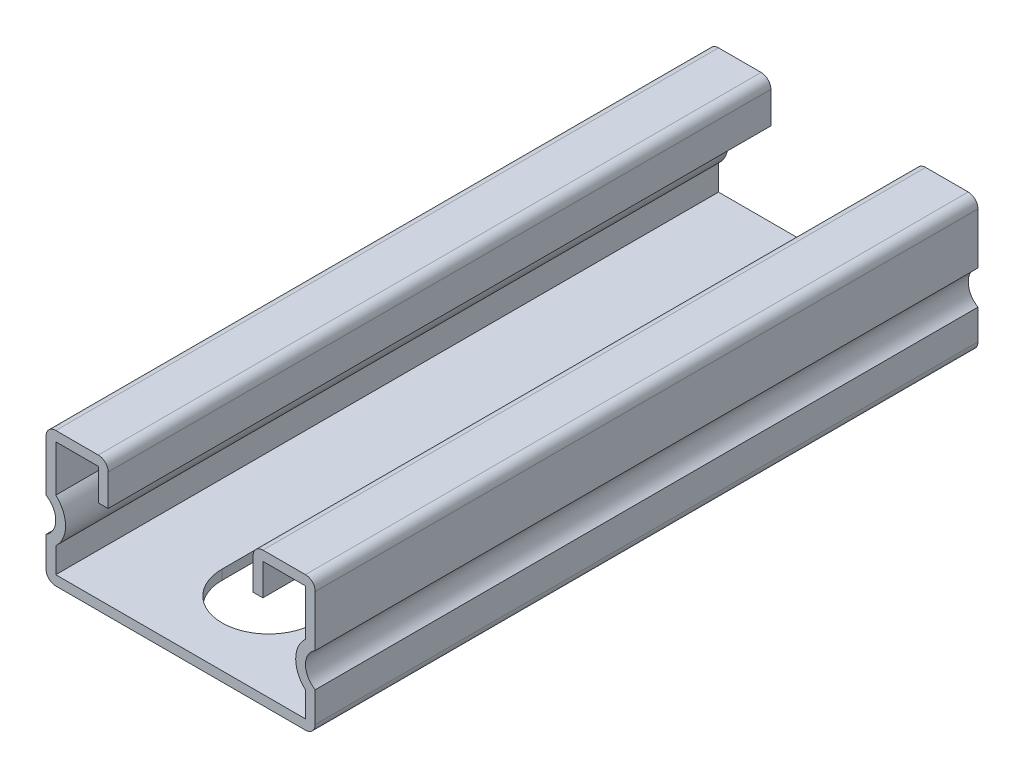
SolidWorks part; units mm, degrees
ref_plane "Plane1" through (0, 0, 0) normal (0, 0, 1) x (1, 0, 0)
ref_plane "Plane2" through (0, 0, 0) normal (0, 1, 0) x (1, 0, 0)
ref_plane "Plane3" through (0, 0, 0) normal (1, 0, 0) x (0, 0, -1)
sketch "Sketch1" plane through (0, 0, 0) normal (0, 0, 1) x (1, 0, 0)
  line L0 (-20.6375, 10.4394) -> (-20.6375, 2.5957)
  line L1 (-20.6375, -2.5957) -> (-20.6375, -7.2136)
  line L2 (-19.1389, -8.7122) -> (19.1389, -8.7122)
  line L3 (20.6375, -7.2136) -> (20.6375, -2.5957)
  line L4 (20.6375, 2.5957) -> (20.6375, 10.4394)
  line L5 (19.1389, 11.938) -> (12.6111, 11.938)
  line L6 (11.1125, 10.4394) -> (11.1125, 5.588)
  line L7 (-19.1389, 11.938) -> (-12.6111, 11.938)
  line L8 (-11.1125, 10.4394) -> (-11.1125, 5.588)
  line L9 (19.1389, -5.2823) -> (19.1389, 6.4389) construction
  line L10 (-19.1389, 6.4389) -> (-19.1389, -5.2823) construction
  line L11 (-12.6111, 10.4394) -> (-12.6111, 5.588)
  line L12 (-19.1389, 10.4394) -> (-12.6111, 10.4394)
  line L13 (-19.1389, 10.4394) -> (-19.1389, 3.351)
  line L14 (-19.1389, -3.351) -> (-19.1389, -7.2136)
  line L15 (-19.1389, -7.2136) -> (19.1389, -7.2136)
  line L16 (19.1389, -7.2136) -> (19.1389, -3.351)
  line L17 (19.1389, 3.351) -> (19.1389, 10.4394)
  line L18 (19.1389, 10.4394) -> (12.6111, 10.4394)
  line L19 (12.6111, 10.4394) -> (12.6111, 5.588)
  line L20 (-12.6111, 5.588) -> (-11.1125, 5.588)
  line L21 (11.1125, 5.588) -> (12.6111, 5.588)
  arc A0 (20.6375, 2.5957) -> (20.6375, -2.5957) centre (22.1361, 0) ccw
  arc A1 (-20.6375, -2.5957) -> (-20.6375, 2.5957) centre (-22.1361, 0) ccw
  arc A2 (-12.6111, 11.938) -> (-11.1125, 10.4394) centre (-12.6111, 10.4394) cw
  arc A3 (-20.6375, 10.4394) -> (-19.1389, 11.938) centre (-19.1389, 10.4394) cw
  arc A4 (-19.1389, -8.7122) -> (-20.6375, -7.2136) centre (-19.1389, -7.2136) cw
  arc A5 (20.6375, -7.2136) -> (19.1389, -8.7122) centre (19.1389, -7.2136) cw
  arc A6 (19.1389, 11.938) -> (20.6375, 10.4394) centre (19.1389, 10.4394) cw
  arc A7 (11.1125, 10.4394) -> (12.6111, 11.938) centre (12.6111, 10.4394) cw
  arc A8 (-19.1389, -3.351) -> (-19.1389, 3.351) centre (-22.1361, 0) ccw
  arc A9 (19.1389, 3.351) -> (19.1389, -3.351) centre (22.1361, 0) ccw
  dimension "D9" = 2.9972
  dimension "D10" = 2.9972
  dimension "D1" = 20.6375
  dimension "Width" = 41.275
  dimension "base" = 8.7122
  dimension "ToeHt" = 11.938
  dimension "D6" = 22.225
  dimension "edge" = 9.525
  dimension "Lip" = 6.35
  dimension "gauge" = 1.4986
extrude "Base-Extrude" add sketch "Sketch1" along normal blind 101.6
extrude "Slot" cut sketch "Sketch2" against normal through all
sketch "Sketch2" plane through (-0.7476, -8.7122, -11.6779) normal (0, -1, 0) x (1, 0, 0)
  line L0 (7.8914, 48.9841) -> (7.8914, 34.6966)
  line L1 (-6.3961, 34.6966) -> (-6.3961, 48.9841)
  arc A0 (-6.3961, 34.6966) -> (7.8914, 34.6966) centre (0.7476, 34.6966) ccw
  arc A1 (7.8914, 48.9841) -> (-6.3961, 48.9841) centre (0.7476, 48.9841) ccw
  dimension "D3" = 14.2875
  dimension "D1" = 23.0188
  dimension "D2" = 14.2875
pattern_linear "LPattern1" count 2 spacing 50.8 along (0, 0, 1) of "Slot"
equation "\"D1@Sketch1\" = \"Width@Sketch1\" / 2"
equation "\"D6@Sketch1\" = \"Width@Sketch1\" - 2 * \"edge@Sketch1\""
equation "\"D10@Sketch1\" = 2 * \"gauge@Sketch1\""
equation "\"D9@Sketch1\" = \"D10@Sketch1\""
equation "\"D1@LPattern1\" = \"D1@Base-Extrude\" / \"D3@LPattern1\""
